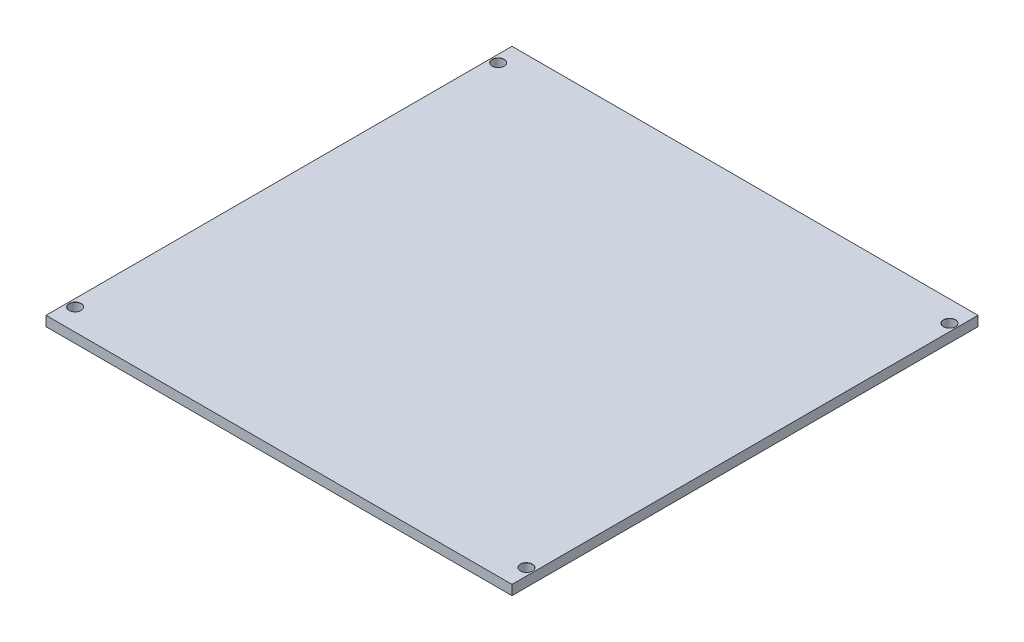
SolidWorks part; units mm, degrees
material "6061-T6 (SS)"
ref_plane "Front Plane" through (0, 0, 0) normal (0, 0, 1) x (1, 0, 0)
ref_plane "Top Plane" through (0, 0, 0) normal (0, 1, 0) x (1, 0, 0)
ref_plane "Right Plane" through (0, 0, 0) normal (1, 0, 0) x (0, 0, -1)
sketch "Sketch2" plane through (0, 0, 0) normal (0, 1, 0) x (1, 0, 0)
  line L1 (-47.375, -47.375) -> (47.375, -47.375)
  line L2 (-47.375, -47.375) -> (-47.375, 47.375)
  line L3 (-47.375, 47.375) -> (47.375, 47.375)
  line L4 (47.375, -47.375) -> (47.375, 47.375)
  line L5 (-47.375, -47.375) -> (47.375, 47.375) construction
  line L6 (-47.375, 47.375) -> (47.375, -47.375) construction
  point P0 (0, 0)
  dimension "D1" = 94.75
  dimension "D2" = 94.75
extrude "Boss-Extrude1" add sketch "Sketch2" along normal blind 2
hole_wizard "M2 Clearance Hole1" positions "Sketch3" profile "Sketch4" hole size "M2" standard "ANSI Metric" end condition up to next
sketch "Sketch3" plane through (0, 2, 0) normal (0, 1, 0) x (1, 0, 0)
  line L0 (-47.375, 47.375) -> (-47.375, -47.375) construction
  line L1 (47.375, -47.375) -> (47.375, 47.375) construction
  point P0 (45.875, 43.0839)
  point P2 (-45.875, 43.072)
  point P4 (-45.875, -42.9412)
  point P6 (45.875, -42.9529)
  dimension "D1" = 1.5
  dimension "D2" = 1.5
  dimension "D3" = 1.5
  dimension "D4" = 1.5
sketch "Sketch4" plane through (45.875, 2, -43.0839) normal (1, 0, 0) x (0, 0, 1)
  line L0 (0, 0) -> (0, 2)
  line L1 (0, 2) -> (1.2, 2)
  line L2 (1.2, 2) -> (1.2, 0.025)
  line L3 (1.2, 0.025) -> (1.225, 0)
  line L5 (1.225, 0) -> (0, 0)
  line L6 (-1.2, 0.025) -> (-1.225, 0) construction
  line L11 (0, -6.35) -> (0, 107.95) construction
  dimension "Thru Hole Dia." = 2.4
  dimension "Thru Hole Depth" = 2
  dimension "Near C'Sink Dia." = 2.45
  dimension "Near C'Sink Angle" = 90
